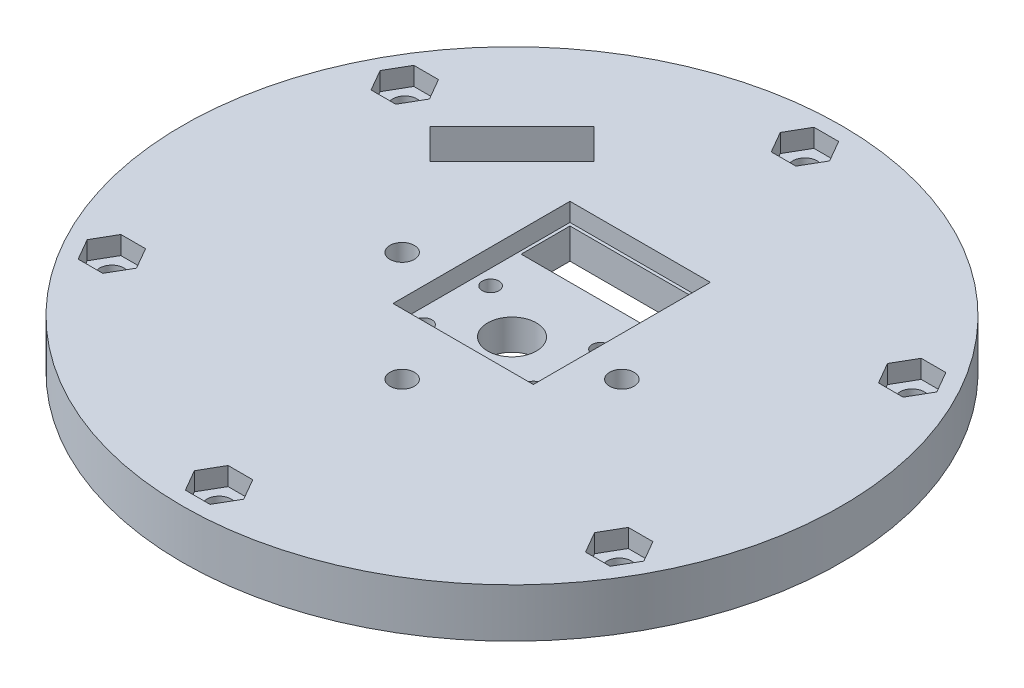
SolidWorks part; units mm, degrees
ref_plane "Front Plane" through (0, 0, 0) normal (0, 0, 1) x (1, 0, 0)
ref_plane "Top Plane" through (0, 0, 0) normal (0, 1, 0) x (1, 0, 0)
ref_plane "Right Plane" through (0, 0, 0) normal (1, 0, 0) x (0, 0, -1)
sketch "Sketch1" plane through (0, 0, 0) normal (0, 1, 0) x (1, 0, 0)
  circle A0 centre (0, 0) radius 48 construction
  circle A1 centre (0, 0) radius 54
  dimension "D1" = 108
  dimension "D2" = 96
extrude "Base Plate" add sketch "Sketch1" along normal blind 8
sketch "Hole Pattern" plane through (0, 0, 0) normal (0, -1, 0) x (1, 0, 0)
  line L0 (-1000, 0) -> (49000, 0) construction
  line L1 (0, 0) -> (-41.5692, 24) construction
  line L2 (0, 0) -> (0, 18) construction
  line L3 (0, 0) -> (18, 0) construction
  circle A0 centre (0, 0) radius 48 construction
  circle A1 centre (0, 48) radius 2
  circle A2 centre (41.5692, 24) radius 2
  circle A3 centre (41.5692, -24) radius 2
  circle A4 centre (0, -48) radius 2
  circle A5 centre (-41.5692, -24) radius 2
  circle A6 centre (-41.5692, 24) radius 2
  circle A7 centre (0, 0) radius 18 construction
  circle A8 centre (0, 18) radius 2
  circle A9 centre (18, 0) radius 2
  circle A10 centre (0, -18) radius 2 [skipped]
  circle A11 centre (-18, 0) radius 2
  dimension "D1" = 96
  dimension "D2" = 4
  dimension "D6" = 36
  dimension "D7" = 4
  dimension "D11" = 18
  dimension "D4" = 48
  dimension "D5" = 30
  dimension "D9" = 90
  dimension "D10" = 18
  dimension "D3" = 6
  dimension "D8" = 4
extrude "Motor Mount Holes" cut sketch "Hole Pattern" against normal through all
sketch "Sketch3" plane through (0, 8, 0) normal (0, 1, 0) x (1, 0, 0)
  line L1 (-9, -5.5) -> (9, -5.5) construction
  line L2 (-9, -5.5) -> (-9, 5.5) construction
  line L3 (-9, 5.5) -> (9, 5.5) construction
  line L4 (9, -5.5) -> (9, 5.5) construction
  line L5 (-9, -5.5) -> (9, 5.5) construction
  line L6 (-9, 5.5) -> (9, -5.5) construction
  circle A0 centre (-9, 5.5) radius 1.375
  circle A1 centre (9, 5.5) radius 1.375
  circle A2 centre (9, -5.5) radius 1.375
  circle A3 centre (-9, -5.5) radius 1.375
  circle A4 centre (0, 0) radius 4
  point P0 (0, 0)
  dimension "D3" = 2.75
  dimension "D4" = 8
  dimension "D1" = 11
  dimension "D2" = 18
extrude "Encoder mounting holes" cut sketch "Sketch3" against normal through all
sketch "Sketch4" plane through (0, 0, 0) normal (0, 1, 0) x (1, 0, 0)
  line L1 (-9, -5.5) -> (9, -5.5) construction
  line L2 (-9, -5.5) -> (-9, 5.5) construction
  line L3 (-9, 5.5) -> (9, 5.5) construction
  line L4 (9, -5.5) -> (9, 5.5) construction
  line L5 (-9, -5.5) -> (9, 5.5) construction
  line L6 (-9, 5.5) -> (9, -5.5) construction
  line L7 (-11, -7.5) -> (11, -7.5) construction
  line L8 (-11, -7.5) -> (-11, 20.5) construction
  line L9 (-11, 20.5) -> (11, 20.5) construction
  line L10 (11, -7.5) -> (11, 20.5) construction
  line L11 (-11, 20.5) -> (11, 20.5)
  line L12 (-11, 20.5) -> (-11, 12.5)
  line L13 (-11, 12.5) -> (11, 12.5)
  line L14 (11, 20.5) -> (11, 12.5)
  point P0 (0, 0)
  dimension "D1" = 22
  dimension "D2" = 28
  dimension "D3" = 2
  dimension "D4" = 2
  dimension "D5" = 8
extrude "Encoder Wire Pass through" cut sketch "Sketch4" along normal blind 5
sketch "Sketch5" plane through (0, 8, 0) normal (0, 1, 0) x (1, 0, 0)
  line L0 (0, 0) -> (-21.9203, 21.9203) construction
  line L1 (-33.5876, 20.1525) -> (-28.6378, 15.2028)
  line L2 (-33.5876, 20.1525) -> (-20.1525, 33.5876)
  line L3 (-28.6378, 15.2028) -> (-15.2028, 28.6378)
  line L4 (-20.1525, 33.5876) -> (-15.2028, 28.6378)
  line L5 (-33.5876, 20.1525) -> (-15.2028, 28.6378) construction
  line L6 (-28.6378, 15.2028) -> (-20.1525, 33.5876) construction
  line L7 (-11, 12.5) -> (11, 12.5) construction
  point P4 (-24.3952, 24.3952)
  point P10 (-21.9203, 21.9203)
  dimension "D1" = 19
  dimension "D2" = 7
  dimension "D3" = 31
  dimension "D4" = 45
  dimension "D5" = 90
extrude "Motor Wire pass through" cut sketch "Sketch5" against normal through all
sketch "Sketch6" plane through (0, 8, 0) normal (0, 1, 0) x (1, 0, 0)
  line L0 (11, 12.5) -> (11, 20.5) construction
  line L2 (-9, 5.5) -> (-9, 12.5) construction
  line L3 (-9, 12.5) -> (9, 12.5) construction
  line L4 (9, 5.5) -> (9, 12.5) construction
  line L5 (-5.9995, 19.5) -> (5.9995, 19.5)
  line L6 (-5.9995, 19.5) -> (-5.9995, 5.5)
  line L7 (-5.9995, 5.5) -> (5.9995, 5.5)
  line L8 (5.9995, 19.5) -> (5.9995, 5.5)
  line L9 (-11, 12.5) -> (11, 12.5) construction
  point P5 (0, 12.5)
  dimension "D1" = 18
  dimension "D2" = 7
  dimension "D3" = 5.0005
  dimension "D4" = 16.9995
  dimension "D5" = 7
extrude "Cut-Extrude6" cut sketch "Sketch6" against normal blind 2
sketch "Sketch7" plane through (0, 0, 0) normal (0, -1, 0) x (1, 0, 0)
  line L1 (7.5566, 3) -> (10.4434, 3)
  line L2 (10.4434, 3) -> (11.8868, 5.5)
  line L3 (11.8868, 5.5) -> (10.4434, 8)
  line L4 (10.4434, 8) -> (7.5566, 8)
  line L5 (7.5566, 8) -> (6.1132, 5.5)
  line L6 (6.1132, 5.5) -> (7.5566, 3)
  line L7 (10.4434, -8) -> (11.8868, -5.5)
  line L8 (11.8868, -5.5) -> (10.4434, -3)
  line L9 (10.4434, -3) -> (7.5566, -3)
  line L10 (7.5566, -3) -> (6.1132, -5.5)
  line L11 (6.1132, -5.5) -> (7.5566, -8)
  line L12 (7.5566, -8) -> (10.4434, -8)
  line L13 (-7.5566, -8) -> (-6.1132, -5.5)
  line L14 (-6.1132, -5.5) -> (-7.5566, -3)
  line L15 (-7.5566, -3) -> (-10.4434, -3)
  line L16 (-10.4434, -3) -> (-11.8868, -5.5)
  line L17 (-11.8868, -5.5) -> (-10.4434, -8)
  line L18 (-10.4434, -8) -> (-7.5566, -8)
  line L19 (-7.5566, 3) -> (-6.1132, 5.5)
  line L20 (-6.1132, 5.5) -> (-7.5566, 8)
  line L21 (-7.5566, 8) -> (-10.4434, 8)
  line L22 (-10.4434, 8) -> (-11.8868, 5.5)
  line L23 (-11.8868, 5.5) -> (-10.4434, 3)
  line L24 (-10.4434, 3) -> (-7.5566, 3)
  circle A0 centre (9, 5.5) radius 2.5 construction
  circle A1 centre (9, -5.5) radius 2.5 construction
  circle A2 centre (-9, -5.5) radius 2.5 construction
  circle A3 centre (-9, 5.5) radius 2.5 construction
  point P1 (6.8349, 6.75)
  dimension "D1" = 5
extrude "Cut-Extrude7" cut sketch "Sketch7" against normal blind 2
sketch "Sketch9" plane through (0, 8, 0) normal (0, -1, 0) x (1, 0, 0)
  line L0 (39.5485, -27.5) -> (43.5899, -27.5)
  line L1 (-4.0415, -48) -> (-2.0207, -51.5)
  line L2 (-2.0207, -51.5) -> (2.0207, -51.5)
  line L3 (2.0207, -51.5) -> (4.0415, -48)
  line L4 (4.0415, -48) -> (2.0207, -44.5)
  line L5 (2.0207, -44.5) -> (-2.0207, -44.5)
  line L6 (-2.0207, -44.5) -> (-4.0415, -48)
  line L7 (43.5899, -27.5) -> (45.6107, -24)
  line L8 (45.6107, -24) -> (43.5899, -20.5)
  line L9 (43.5899, -20.5) -> (39.5485, -20.5)
  line L10 (39.5485, -20.5) -> (37.5278, -24)
  line L11 (37.5278, -24) -> (39.5485, -27.5)
  line L12 (43.5899, 20.5) -> (45.6107, 24)
  line L13 (45.6107, 24) -> (43.5899, 27.5)
  line L14 (43.5899, 27.5) -> (39.5485, 27.5)
  line L15 (39.5485, 27.5) -> (37.5278, 24)
  line L16 (37.5278, 24) -> (39.5485, 20.5)
  line L17 (39.5485, 20.5) -> (43.5899, 20.5)
  line L18 (4.0415, 48) -> (2.0207, 51.5)
  line L19 (2.0207, 51.5) -> (-2.0207, 51.5)
  line L20 (-2.0207, 51.5) -> (-4.0415, 48)
  line L21 (-4.0415, 48) -> (-2.0207, 44.5)
  line L22 (-2.0207, 44.5) -> (2.0207, 44.5)
  line L23 (2.0207, 44.5) -> (4.0415, 48)
  line L24 (-39.5485, 27.5) -> (-43.5899, 27.5)
  line L25 (-43.5899, 27.5) -> (-45.6107, 24)
  line L26 (-45.6107, 24) -> (-43.5899, 20.5)
  line L27 (-43.5899, 20.5) -> (-39.5485, 20.5)
  line L28 (-39.5485, 20.5) -> (-37.5278, 24)
  line L29 (-37.5278, 24) -> (-39.5485, 27.5)
  line L30 (-43.5899, -20.5) -> (-45.6107, -24)
  line L31 (-45.6107, -24) -> (-43.5899, -27.5)
  line L32 (-43.5899, -27.5) -> (-39.5485, -27.5)
  line L33 (-39.5485, -27.5) -> (-37.5278, -24)
  line L34 (-37.5278, -24) -> (-39.5485, -20.5)
  line L35 (-39.5485, -20.5) -> (-43.5899, -20.5)
  circle A0 centre (0, -48) radius 3.5 construction
  dimension "D1" = 7
  dimension "D2" = 6
extrude "Cut-Extrude8" cut sketch "Sketch9" along normal blind 3
sketch "Sketch10" plane through (0, 8, 0) normal (0, 1, 0) x (1, 0, 0)
  line L0 (-11, 20.5) -> (-11, 12.5) construction
  line L1 (-11.5, 21) -> (11.5, 21)
  line L2 (-11.5, 21) -> (-11.5, -8)
  line L3 (-11.5, -8) -> (11.5, -8)
  line L4 (11.5, 21) -> (11.5, -8)
  line L5 (11, 20.5) -> (-11, 20.5) construction
  dimension "D1" = 23
  dimension "D2" = 29
  dimension "D3" = 0.5
  dimension "D4" = 0.5
extrude "Cut-Extrude9" cut sketch "Sketch10" against normal blind 3
ref_plane "Plane2" through (4.75, 0, -4.75) normal (-0.7071, 0, 0.7071) x (0.7071, 0, 0.7071)
sketch "Sketch11" plane through (6.7175, 0, -6.7175) normal (-0.7071, 0, 0.7071) x (0.7071, 0, 0.7071)
  line L0 (676.1068, -707.1068) -> (-34679.2323, 34648.2323) construction
  line L1 (-1000, 0) -> (49000, 0) construction
  dimension "D1" = 45
equation "\"encoderCutout\"=3"
equation "\"D1@Cut-Extrude9\"=\"encoderCutout\""
equation "\"encoderAirGap\"=5"
equation "\"D1@Encoder Wire Pass through\"=\"encoderAirGap\""
equation "\"D1@Base Plate\"=\"encoderCutout\"+\"encoderAirGap\""
